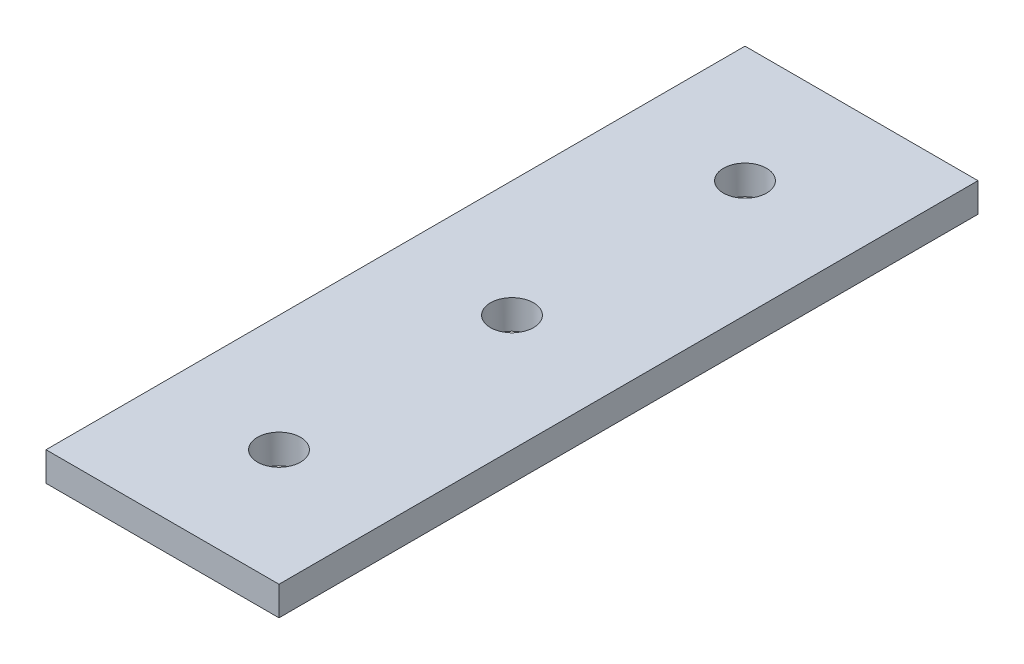
SolidWorks part; units mm, degrees
ref_plane "Front Plane" through (0, 0, 0) normal (0, 0, 1) x (1, 0, 0)
ref_plane "Top Plane" through (0, 0, 0) normal (0, 1, 0) x (1, 0, 0)
ref_plane "Right Plane" through (0, 0, 0) normal (1, 0, 0) x (0, 0, -1)
sketch "Sketch1" plane through (0, 0, 0) normal (0, 1, 0) x (1, 0, 0)
  line L1 (-12.7, -38.1) -> (12.7, -38.1)
  line L2 (-12.7, -38.1) -> (-12.7, 38.1)
  line L3 (-12.7, 38.1) -> (12.7, 38.1)
  line L4 (12.7, -38.1) -> (12.7, 38.1)
  line L5 (-12.7, -38.1) -> (12.7, 38.1) construction
  line L6 (-12.7, 38.1) -> (12.7, -38.1) construction
  point P0 (0, 0)
  dimension "D1" = 25.4
  dimension "D2" = 76.2
extrude "Boss-Extrude1" add sketch "Sketch1" along normal mid plane 3.175 contours L3 L4 L1 L2
sketch "Sketch2" plane through (0, 1.5875, 0) normal (0, 1, 0) x (1, 0, 0)
  line L0 (0, 25.4) -> (0, -25.4) construction
  line L1 (-12.7, -38.1) -> (12.7, -38.1) construction
  circle A0 centre (0, -25.4) radius 2.3495
  circle A1 centre (0, 0) radius 2.3495
  circle A2 centre (0, 25.4) radius 2.3495
  point P9 (0, 0)
  point P10 (0, 0)
  dimension "D1" = 4.699
  dimension "D2" = 12.7
extrude "Cut-Extrude1" cut sketch "Sketch2" against normal through all both and the other way through all
